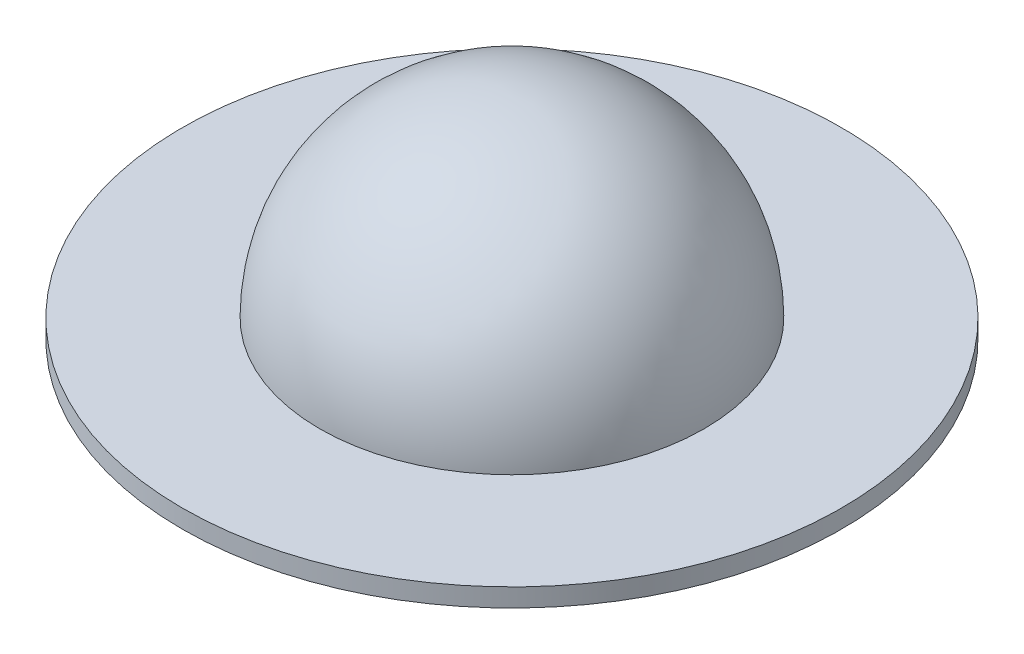
SolidWorks part; units mm, degrees
ref_plane "Front Plane" through (0, 0, 0) normal (0, 0, 1) x (1, 0, 0)
ref_plane "Top Plane" through (0, 0, 0) normal (0, 1, 0) x (1, 0, 0)
ref_plane "Right Plane" through (0, 0, 0) normal (1, 0, 0) x (0, 0, -1)
sketch "Sketch1" plane through (0, 0, 0) normal (0, 1, 0) x (1, 0, 0)
  circle A0 centre (0, 0) radius 72
  dimension "D1" = 144
extrude "Boss-Extrude1" add sketch "Sketch1" along normal blind 4
sketch "Sketch2" plane through (0, 0, 0) normal (0, 0, 1) x (1, 0, 0)
  line L0 (0, 4) -> (0, 46)
  line L1 (72, 4) -> (-72, 4) construction
  line L2 (0, 4) -> (42, 4)
  arc A0 (0, 46) -> (42, 4) centre (0, 4) cw
  dimension "D1" = 42
revolve "Revolve1" add sketch "Sketch2" angle 360 about L0
